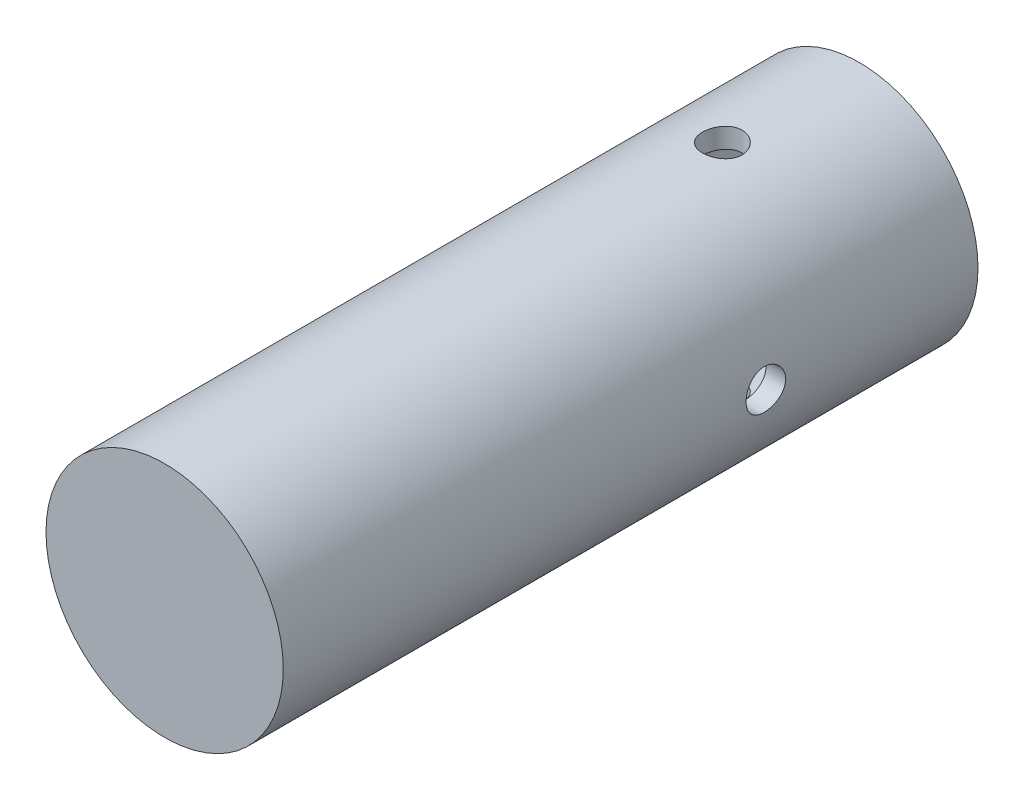
SolidWorks part; units mm, degrees
material "AISI 4130 Steel, annealed at 865C"
ref_plane "X-Y Datum" through (0, 0, 0) normal (0, 0, 1) x (1, 0, 0)
ref_plane "X-Z Datum" through (0, 0, 0) normal (0, 1, 0) x (1, 0, 0)
ref_plane "Y-Z Datum" through (0, 0, 0) normal (1, 0, 0) x (0, 0, -1)
sketch "Sketch9" plane through (0, 0, 0) normal (0, 1, 0) x (1, 0, 0)
  line L0 (16.002, 0) -> (0, 0)
  line L1 (0, 0) -> (0, -389.0916)
  line L2 (0, -389.0916) -> (-72.2493, -524.9728)
  dimension "D1" = 153.895
  dimension "D2" = 28
  dimension "D3" = 389.0916
  dimension "D5" = 16.002
sketch "Sketch5" plane through (0, 0, 0) normal (0, 1, 0) x (1, 0, 0)
  line L0 (7.9375, -77.9416) -> (7.9375, -22.1615)
  line L1 (7.9375, -22.1615) -> (9.525, -22.1615)
  line L2 (9.525, -22.1615) -> (9.525, -77.9416)
  line L3 (9.525, -77.9416) -> (7.9375, -77.9416)
  line L5 (16.002, 0) -> (0, 0) construction
  line L6 (0, 0) -> (0, -389.0916) construction
  line L7 (0, -389.0916) -> (9.525, -389.0916) construction
  line L8 (12.5602, -58.6916) -> (0, -58.6916) construction
  dimension "D1" = 1.5875
  dimension "D2" = 22.1615
  dimension "D3" = 7.9375
  dimension "D4" = 330.4
  dimension "D5" = 311.15
revolve "Revolve2" add sketch "Sketch5" angle 360 about L1
sketch "Sketch6" plane through (0, 0, 0) normal (0, 1, 0) x (1, 0, 0)
  circle A0 centre (0, -33.1635) radius 1.5875 construction
  circle A1 centre (0, -33.1635) radius 1.5875
sketch "Sketch7" plane through (0, 0, 0) normal (1, 0, 0) x (0, 0, -1)
  circle A2 centre (-39.196, 0) radius 1.5875
  circle A4 centre (-39.196, 0) radius 1.5875 construction
extrude "Cut-Extrude5" cut sketch "Sketch7" against normal through all both and the other way through all
extrude "Cut-Extrude6" cut sketch "Sketch6" against normal through all both and the other way through all
sketch "Sketch8" plane through (0, 0, 0) normal (0, 0, 1) x (1, 0, 0)
  line L0 (9.2357, -0.808) -> (8.6817, -0.254)
  line L1 (8.6817, -0.254) -> (8.6817, 0.254)
  line L2 (8.6817, 0.254) -> (9.2357, 0.808)
  line L3 (8.6817, 0) -> (0, 0) construction
  line L4 (8.9551, -2.3995) -> (8.5057, -1.7577)
  line L5 (8.5057, -1.7577) -> (8.5939, -1.2574)
  line L6 (8.5939, -1.2574) -> (9.2357, -0.808)
  line L7 (8.4024, -3.9181) -> (8.0713, -3.208)
  line L8 (8.0713, -3.208) -> (8.245, -2.7306)
  line L9 (8.245, -2.7306) -> (8.9551, -2.3995)
  line L10 (7.5944, -5.3176) -> (7.3916, -4.5608)
  line L11 (7.3916, -4.5608) -> (7.6456, -4.1209)
  line L12 (7.6456, -4.1209) -> (8.4024, -3.9181)
  line L13 (6.5556, -6.5556) -> (6.4873, -5.7751)
  line L14 (6.4873, -5.7751) -> (6.8138, -5.3859)
  line L15 (6.8138, -5.3859) -> (7.5944, -5.3176)
  line L16 (5.3176, -7.5944) -> (5.3859, -6.8138)
  line L17 (5.3859, -6.8138) -> (5.7751, -6.4873)
  line L18 (5.7751, -6.4873) -> (6.5556, -6.5556)
  line L19 (3.9181, -8.4024) -> (4.1209, -7.6456)
  line L20 (4.1209, -7.6456) -> (4.5608, -7.3916)
  line L21 (4.5608, -7.3916) -> (5.3176, -7.5944)
  line L22 (2.3995, -8.9551) -> (2.7306, -8.245)
  line L23 (2.7306, -8.245) -> (3.208, -8.0713)
  line L24 (3.208, -8.0713) -> (3.9181, -8.4024)
  line L25 (0.808, -9.2357) -> (1.2574, -8.5939)
  line L26 (1.2574, -8.5939) -> (1.7577, -8.5057)
  line L27 (1.7577, -8.5057) -> (2.3995, -8.9551)
  line L28 (-0.808, -9.2357) -> (-0.254, -8.6817)
  line L29 (-0.254, -8.6817) -> (0.254, -8.6817)
  line L30 (0.254, -8.6817) -> (0.808, -9.2357)
  line L31 (-2.3995, -8.9551) -> (-1.7577, -8.5057)
  line L32 (-1.7577, -8.5057) -> (-1.2574, -8.5939)
  line L33 (-1.2574, -8.5939) -> (-0.808, -9.2357)
  line L34 (-3.9181, -8.4024) -> (-3.208, -8.0713)
  line L35 (-3.208, -8.0713) -> (-2.7306, -8.245)
  line L36 (-2.7306, -8.245) -> (-2.3995, -8.9551)
  line L37 (-5.3176, -7.5944) -> (-4.5608, -7.3916)
  line L38 (-4.5608, -7.3916) -> (-4.1209, -7.6456)
  line L39 (-4.1209, -7.6456) -> (-3.9181, -8.4024)
  line L40 (-6.5556, -6.5556) -> (-5.7751, -6.4873)
  line L41 (-5.7751, -6.4873) -> (-5.3859, -6.8138)
  line L42 (-5.3859, -6.8138) -> (-5.3176, -7.5944)
  line L43 (-7.5944, -5.3176) -> (-6.8138, -5.3859)
  line L44 (-6.8138, -5.3859) -> (-6.4873, -5.7751)
  line L45 (-6.4873, -5.7751) -> (-6.5556, -6.5556)
  line L46 (-8.4024, -3.9181) -> (-7.6456, -4.1209)
  line L47 (-7.6456, -4.1209) -> (-7.3916, -4.5608)
  line L48 (-7.3916, -4.5608) -> (-7.5944, -5.3176)
  line L49 (-8.9551, -2.3995) -> (-8.245, -2.7306)
  line L50 (-8.245, -2.7306) -> (-8.0713, -3.208)
  line L51 (-8.0713, -3.208) -> (-8.4024, -3.9181)
  line L52 (-9.2357, -0.808) -> (-8.5939, -1.2574)
  line L53 (-8.5939, -1.2574) -> (-8.5057, -1.7577)
  line L54 (-8.5057, -1.7577) -> (-8.9551, -2.3995)
  line L55 (-9.2357, 0.808) -> (-8.6817, 0.254)
  line L56 (-8.6817, 0.254) -> (-8.6817, -0.254)
  line L57 (-8.6817, -0.254) -> (-9.2357, -0.808)
  line L58 (-8.9551, 2.3995) -> (-8.5057, 1.7577)
  line L59 (-8.5057, 1.7577) -> (-8.5939, 1.2574)
  line L60 (-8.5939, 1.2574) -> (-9.2357, 0.808)
  line L61 (-8.4024, 3.9181) -> (-8.0713, 3.208)
  line L62 (-8.0713, 3.208) -> (-8.245, 2.7306)
  line L63 (-8.245, 2.7306) -> (-8.9551, 2.3995)
  line L64 (-7.5944, 5.3176) -> (-7.3916, 4.5608)
  line L65 (-7.3916, 4.5608) -> (-7.6456, 4.1209)
  line L66 (-7.6456, 4.1209) -> (-8.4024, 3.9181)
  line L67 (-6.5556, 6.5556) -> (-6.4873, 5.7751)
  line L68 (-6.4873, 5.7751) -> (-6.8138, 5.3859)
  line L69 (-6.8138, 5.3859) -> (-7.5944, 5.3176)
  line L70 (-5.3176, 7.5944) -> (-5.3859, 6.8138)
  line L71 (-5.3859, 6.8138) -> (-5.7751, 6.4873)
  line L72 (-5.7751, 6.4873) -> (-6.5556, 6.5556)
  line L73 (-3.9181, 8.4024) -> (-4.1209, 7.6456)
  line L74 (-4.1209, 7.6456) -> (-4.5608, 7.3916)
  line L75 (-4.5608, 7.3916) -> (-5.3176, 7.5944)
  line L76 (-2.3995, 8.9551) -> (-2.7306, 8.245)
  line L77 (-2.7306, 8.245) -> (-3.208, 8.0713)
  line L78 (-3.208, 8.0713) -> (-3.9181, 8.4024)
  line L79 (-0.808, 9.2357) -> (-1.2574, 8.5939)
  line L80 (-1.2574, 8.5939) -> (-1.7577, 8.5057)
  line L81 (-1.7577, 8.5057) -> (-2.3995, 8.9551)
  line L82 (0.808, 9.2357) -> (0.254, 8.6817)
  line L83 (0.254, 8.6817) -> (-0.254, 8.6817)
  line L84 (-0.254, 8.6817) -> (-0.808, 9.2357)
  line L85 (2.3995, 8.9551) -> (1.7577, 8.5057)
  line L86 (1.7577, 8.5057) -> (1.2574, 8.5939)
  line L87 (1.2574, 8.5939) -> (0.808, 9.2357)
  line L88 (3.9181, 8.4024) -> (3.208, 8.0713)
  line L89 (3.208, 8.0713) -> (2.7306, 8.245)
  line L90 (2.7306, 8.245) -> (2.3995, 8.9551)
  line L91 (5.3176, 7.5944) -> (4.5608, 7.3916)
  line L92 (4.5608, 7.3916) -> (4.1209, 7.6456)
  line L93 (4.1209, 7.6456) -> (3.9181, 8.4024)
  line L94 (6.5556, 6.5556) -> (5.7751, 6.4873)
  line L95 (5.7751, 6.4873) -> (5.3859, 6.8138)
  line L96 (5.3859, 6.8138) -> (5.3176, 7.5944)
  line L97 (7.5944, 5.3176) -> (6.8138, 5.3859)
  line L98 (6.8138, 5.3859) -> (6.4873, 5.7751)
  line L99 (6.4873, 5.7751) -> (6.5556, 6.5556)
  line L100 (8.4024, 3.9181) -> (7.6456, 4.1209)
  line L101 (7.6456, 4.1209) -> (7.3916, 4.5608)
  line L102 (7.3916, 4.5608) -> (7.5944, 5.3176)
  line L103 (8.9551, 2.3995) -> (8.245, 2.7306)
  line L104 (8.245, 2.7306) -> (8.0713, 3.208)
  line L105 (8.0713, 3.208) -> (8.4024, 3.9181)
  line L106 (9.2357, 0.808) -> (8.5939, 1.2574)
  line L107 (8.5939, 1.2574) -> (8.5057, 1.7577)
  line L108 (8.5057, 1.7577) -> (8.9551, 2.3995)
  circle A0 centre (0, 0) radius 12.7
  circle A1 centre (0, 0) radius 9.271 construction
  circle A2 centre (0, 0) radius 8.6854 construction
  point P153 (0, 0)
  dimension "D1" = 25.4
  dimension "D4" = 18.542
  dimension "D6" = 17.3708
  dimension "D2" = 0.508
  dimension "D3" = 135
  dimension "D5" = 36
ref_plane "Plane1" through (0, 0, 47.5615) normal (0, 0, -1) x (-1, 0, 0)
sketch "Sketch10" plane through (0, 0, 47.5615) normal (0, 0, -1) x (-1, 0, 0)
  circle A0 centre (0, 0) radius 7.9375
  dimension "D1" = 15.875
extrude "Boss-Extrude1" add sketch "Sketch10" against normal up to surface (30.3801 mm away) up to face at (-9.525, 0, 77.9416)
sketch "Sketch11" plane through (0, 0, 22.1615) normal (0, 0, -1) x (-1, 0, 0)
  line L0 (0, 9.525) -> (13.3548, 9.525) construction
  line L1 (0, 9.525) -> (0, 15.4312) construction
  line L2 (-9.525, 0) -> (-9.525, 9.1744) construction
  line L3 (-9.525, 0) -> (-16.674, 0) construction
  circle A0 centre (0, 0) radius 9.525 construction
  point P0 (0, 9.525)
  point P1 (-9.525, 0)
